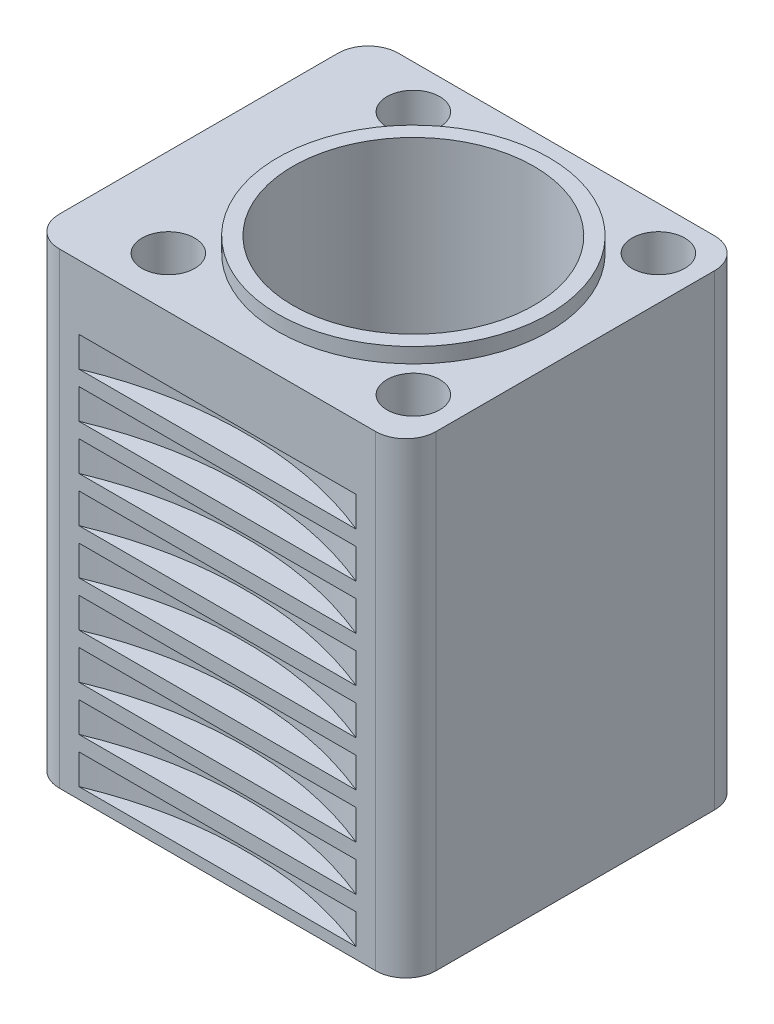
SolidWorks part; units mm, degrees
ref_plane "Front Plane" through (0, 0, 0) normal (0, 0, 1) x (1, 0, 0)
ref_plane "Top Plane" through (0, 0, 0) normal (0, 1, 0) x (1, 0, 0)
ref_plane "Right Plane" through (0, 0, 0) normal (1, 0, 0) x (0, 0, -1)
sketch "Sketch1" plane through (0, 0, 0) normal (0, 1, 0) x (1, 0, 0)
  line L1 (-24, 22) -> (18, 22)
  line L2 (-28, 18) -> (-28, -19)
  line L3 (-24, -23) -> (18, -23)
  line L4 (22, 18) -> (22, -19)
  line L5 (-28, 22) -> (22, -23) construction
  line L6 (-28, -23) -> (22, 22) construction
  arc A0 (-28, -19) -> (-24, -23) centre (-24, -19) ccw
  arc A1 (18, -23) -> (22, -19) centre (18, -19) ccw
  arc A2 (18, 22) -> (22, 18) centre (18, 18) cw
  arc A3 (-24, 22) -> (-28, 18) centre (-24, 18) ccw
  point P0 (0, 0)
  point P18 (0, 0)
  point P19 (0, 0)
  dimension "D3" = 4
  dimension "D1" = 50
  dimension "D2" = 45
  dimension "D4" = 22
  dimension "D5" = 22
extrude "Boss-Extrude1" add sketch "Sketch1" along normal blind 62
sketch "Sketch2" plane through (0, 62, 0) normal (0, 1, 0) x (1, 0, 0)
  circle A0 centre (0, 0) radius 18
  dimension "D1" = 36
extrude "Boss-Extrude2" add sketch "Sketch2" along normal blind 2
sketch "Sketch3" plane through (0, 64, 0) normal (0, 1, 0) x (1, 0, 0)
  circle A0 centre (0, 0) radius 16
  dimension "D1" = 32
extrude "Cut-Extrude1" cut sketch "Sketch3" against normal through all
sketch "Sketch4" plane through (0, 0, 0) normal (0, -1, 0) x (1, 0, 0)
  line L0 (-20.3069, -1.9941) -> (-20.3069, -2)
  line L1 (-20.3069, 2) -> (-10.4438, 2)
  line L2 (-20.3069, 2) -> (-20.3069, 1.9941)
  line L3 (-20.3069, -2) -> (-10.4438, -2)
  line L4 (-10.4438, 2) -> (-10.4438, -2)
  arc A0 (-20.3069, 1.9941) -> (-20.3069, -1.9941) centre (-20.3069, 0) ccw
  dimension "D1" = 4
  dimension "D2" = 2
extrude "Cut-Extrude2" cut sketch "Sketch4" against normal blind 2 contours L1 L4 L3 L0 A0 L2
sketch "Sketch5" plane through (0, 0, 0) normal (0, -1, 0) x (1, 0, 0)
  line L0 (16.2635, 16.2635) -> (0, 0) construction
  line L1 (0, 0) -> (11.5775, 0) construction
  circle A0 centre (0, 0) radius 23 construction
  circle A1 centre (16.2635, 16.2635) radius 3.5
  circle A2 centre (16.2635, -16.2635) radius 3.5
  circle A3 centre (-16.2635, -16.2635) radius 3.5
  circle A4 centre (-16.2635, 16.2635) radius 3.5
  point P16 (0, 0)
  dimension "D1" = 46
  dimension "D2" = 7
  dimension "D3" = 45
  dimension "D4" = 4
extrude "Cut-Extrude3" cut sketch "Sketch5" against normal through all
ref_plane "Plane1" through (-3, 0, 0) normal (1, 0, 0) x (0, 0, -1)
sketch "Sketch7" plane through (-3, 0, 0) normal (1, 0, 0) x (0, 0, -1)
  line L1 (19.3263, 5.4793) -> (67.3263, 5.4793)
  line L2 (19.3263, 5.4793) -> (19.3263, 1.4793)
  line L3 (19.3263, 1.4793) -> (67.3263, 1.4793)
  line L4 (67.3263, 5.4793) -> (67.3263, 1.4793)
  dimension "D1" = 4
  dimension "D2" = 48
revolve "Cut-Revolve1" cut sketch "Sketch7" angle 360 about L4
pattern_linear "LPattern1" count 9 spacing 6 along (0, 1, 0) of "Cut-Revolve1"
mirror "Mirror1" about plane through (0, 0, 0) normal (0, 0, 1) of "LPattern1", "Cut-Revolve1"
sketch "Sketch10" plane through (0, 0, 0) normal (0, 0, 1) x (1, 0, 0)
  line L1 (-25.1359, 5.3694) -> (-73.1359, 5.3694)
  line L2 (-25.1359, 5.3694) -> (-25.1359, 1.3694)
  line L3 (-25.1359, 1.3694) -> (-73.1359, 1.3694)
  line L4 (-73.1359, 5.3694) -> (-73.1359, 1.3694)
  dimension "D2" = 4
  dimension "D3" = 48
revolve "Cut-Revolve2" cut sketch "Sketch10" angle 360 about L4
pattern_linear "LPattern2" count 9 spacing 6 along (0, 1, 0) of "Cut-Revolve2"
